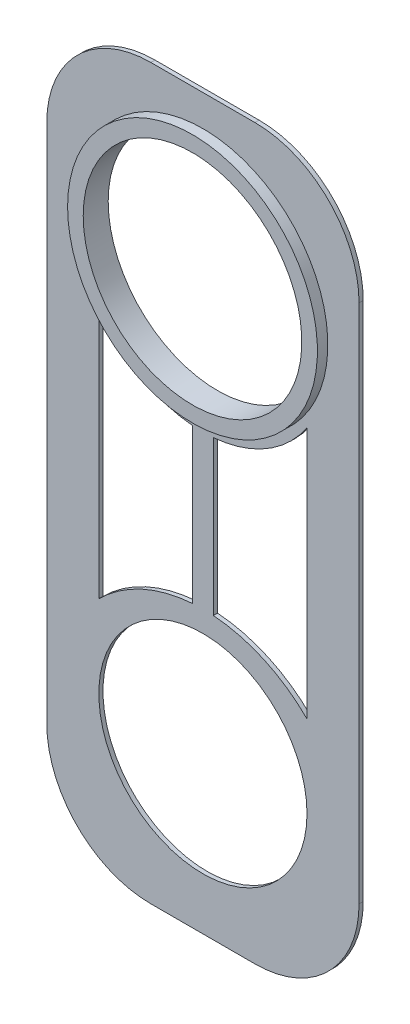
SolidWorks part; units mm, degrees
material "ASTM A36 Steel"
ref_plane "Front Plane" through (0, 0, 0) normal (0, 0, 1) x (1, 0, 0)
ref_plane "Top Plane" through (0, 0, 0) normal (0, 1, 0) x (1, 0, 0)
ref_plane "Right Plane" through (0, 0, 0) normal (1, 0, 0) x (0, 0, -1)
sketch "Sketch2" plane through (0, 0, 0) normal (0, 0, 1) x (1, 0, 0)
  line L0 (19.05, 88.9) -> (19.05, 0) construction
  line L1 (12.7, 0) -> (25.4, 0)
  line L2 (0, 12.7) -> (0, 76.2)
  line L3 (12.7, 88.9) -> (25.4, 88.9)
  line L4 (38.1, 12.7) -> (38.1, 76.2)
  line L5 (0, 19.05) -> (38.1, 19.05) construction
  line L6 (0, 69.85) -> (38.1, 69.85) construction
  arc A0 (0, 12.7) -> (12.7, 0) centre (12.7, 12.7) ccw
  arc A1 (25.4, 0) -> (38.1, 12.7) centre (25.4, 12.7) ccw
  arc A2 (38.1, 76.2) -> (25.4, 88.9) centre (25.4, 76.2) ccw
  arc A3 (12.7, 88.9) -> (0, 76.2) centre (12.7, 76.2) ccw
  circle A4 centre (19.05, 69.85) radius 13.335
  circle A5 centre (19.05, 19.05) radius 12.7
  point P7 (0, 0)
  point P10 (38.1, 0)
  point P13 (38.1, 88.9)
  point P16 (0, 88.9)
  dimension "D3" = 12.7
  dimension "D6" = 26.67
  dimension "D7" = 25.4
  dimension "D1" = 88.9
  dimension "D2" = 38.1
  dimension "D4" = 19.05
  dimension "D5" = 19.05
extrude "Boss-Extrude1" add sketch "Sketch2" along normal blind 0.508
sketch "Sketch3" plane through (0, 0, 0) normal (0, 0, -1) x (-1, 0, 0)
  circle A0 centre (-19.05, 69.85) radius 15.24
  circle A1 centre (-19.05, 69.85) radius 13.335
  dimension "D1" = 30.48
extrude "Boss-Extrude2" add sketch "Sketch3" along normal blind 1.27
ref_plane "Plane1" through (0, 0, 0.254) normal (0, 0, -1) x (-1, 0, 0)
mirror "Mirror1" about plane through (0, 0, 0.254) normal (0, 0, -1) of "Boss-Extrude2"
sketch "Sketch4" plane through (0, 0, 0) normal (0, 0, -1) x (-1, 0, 0)
  line L0 (-31.75, 44.45) -> (-6.35, 44.45) construction
  line L2 (-31.75, 12.7) -> (-31.75, 76.2)
  line L3 (-31.75, 29.0589) -> (-31.75, 59.8411)
  line L5 (-6.35, 76.2) -> (-6.35, 12.7)
  line L6 (-6.35, 59.8411) -> (-6.35, 29.0589)
  arc A0 (-31.75, 29.0589) -> (-6.35, 29.0589) centre (-19.05, 16.3589) cw
  arc A1 (-31.75, 59.8411) -> (-6.35, 59.8411) centre (-19.05, 68.2653) ccw
  dimension "D3" = 15.24
  dimension "D1" = 6.35
  dimension "D2" = 6.35
extrude "Cut-Extrude1" cut sketch "Sketch4" against normal through all
sketch "Sketch5" plane through (0, 0, 0) normal (0, 0, -1) x (-1, 0, 0)
  line L0 (-19.05, 53.0253) -> (-19.05, 34.3194) construction
  line L1 (-20.32, 53.0253) -> (-20.32, 34.3194)
  line L2 (-17.78, 53.0253) -> (-17.78, 34.3194)
  line L3 (-17.78, 34.3194) -> (-17.78, 34.2312)
  line L4 (-20.32, 34.3194) -> (-20.32, 34.1627)
  line L5 (-20.32, 34.1627) -> (-17.78, 34.1627)
  line L6 (-17.78, 34.1627) -> (-17.78, 34.2312)
  line L7 (-17.78, 53.0253) -> (-17.78, 53.1719)
  line L8 (-17.78, 53.1719) -> (-20.32, 53.1719)
  line L9 (-20.32, 53.1719) -> (-20.32, 53.0253)
  arc A0 (-31.75, 59.8411) -> (-6.35, 59.8411) centre (-19.05, 68.2653) ccw construction
  arc A1 (-6.35, 29.0589) -> (-31.75, 29.0589) centre (-19.05, 16.3589) ccw construction
  dimension "D1" = 1.27
  dimension "D2" = 1.27
extrude "Boss-Extrude3" add sketch "Sketch5" against normal blind 0.508
equation "\"F\"= 650"
equation "\"Sy\"= 36000"
equation "\"stress\"= 9000"
equation "\"E\"= 29 * 10 ^ 6"
equation "\"deflection\"= 0.005"
equation "\"w\"= 0.02"
equation "\"h\"= 3.5"
equation "\"d_shaft\"= 1"
equation "\"d_part\"= 1.05"
